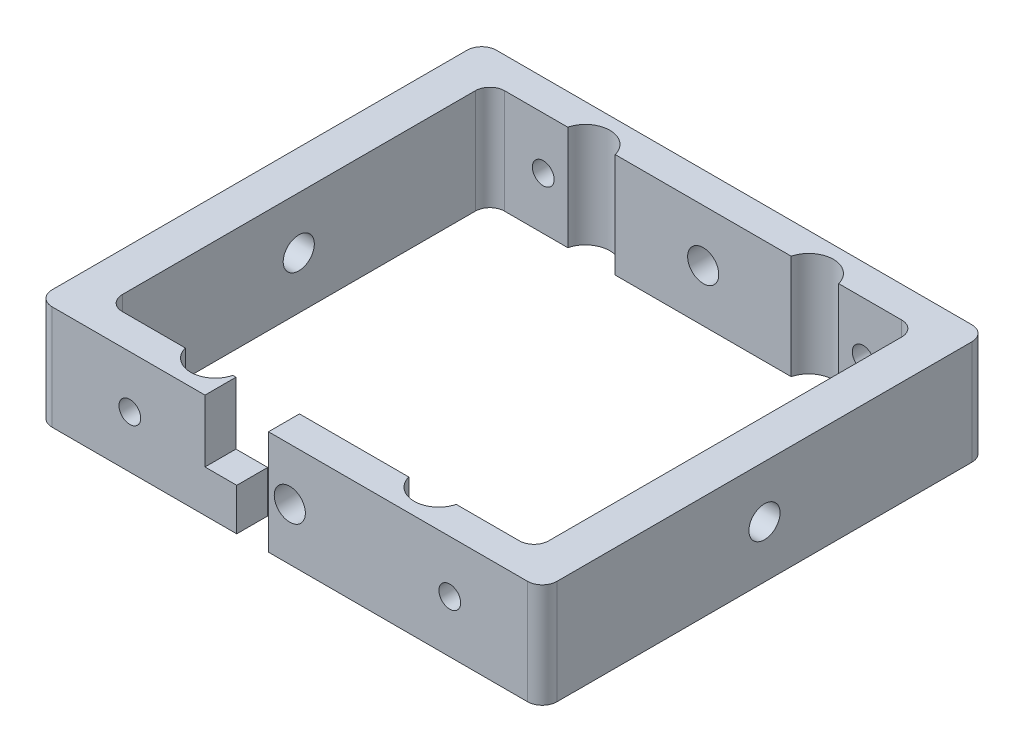
SolidWorks part; units mm, degrees
ref_plane "Front Plane" through (0, 0, 0) normal (0, 0, 1) x (1, 0, 0)
ref_plane "Top Plane" through (0, 0, 0) normal (0, 1, 0) x (1, 0, 0)
ref_plane "Right Plane" through (0, 0, 0) normal (1, 0, 0) x (0, 0, -1)
sketch "Sketch1" plane through (0, 0, 0) normal (0, 1, 0) x (1, 0, 0)
  line L1 (0, 0) -> (60, 0)
  line L2 (0, 0) -> (0, -6.32)
  line L3 (0, -6.32) -> (60, -6.32)
  line L4 (60, 0) -> (60, -6.32)
  dimension "D1" = 60
  dimension "D2" = 6.32
extrude "Boss-Extrude1" add sketch "Sketch1" along normal mid plane 21.28
sketch "Sketch2" plane through (0, 10.64, 0) normal (0, 1, 0) x (1, 0, 0)
  line L0 (0, 0) -> (0, -6.32) construction
  line L1 (0, -6.32) -> (60, -6.32) construction
  line L2 (60, -6.32) -> (60, 0) construction
  circle A0 centre (7.21, 1.25) radius 5
  circle A1 centre (52.79, 1.25) radius 5
  dimension "D1" = 7.21
  dimension "D3" = 7.21
  dimension "D2" = 7.57
  dimension "D4" = 7.57
extrude "Cut-Extrude1" cut sketch "Sketch2" against normal through all
sketch "Sketch3" plane through (60, 0, 0) normal (1, 0, 0) x (0, 0, -1)
  line L1 (-6.32, 10.64) -> (0, 10.64)
  line L2 (-6.32, 10.64) -> (-6.32, -10.64)
  line L3 (-6.32, -10.64) -> (0, -10.64)
  line L4 (0, 10.64) -> (0, -10.64)
extrude "Boss-Extrude2" add sketch "Sketch3" along normal blind 21.5
sketch "Sketch4" plane through (0, 0, 0) normal (-1, 0, 0) x (0, 0, 1)
  line L1 (0, 10.64) -> (6.32, 10.64)
  line L2 (0, 10.64) -> (0, -10.64)
  line L3 (0, -10.64) -> (6.32, -10.64)
  line L4 (6.32, 10.64) -> (6.32, -10.64)
extrude "Boss-Extrude3" add sketch "Sketch4" along normal blind 21.5
sketch "Sketch5" plane through (0, 0, 0) normal (0, 0, -1) x (-1, 0, 0)
  line L5 (-2.3688, -10.64) -> (21.5, -10.64) construction
  line L6 (21.5, 10.64) -> (13.5, 10.64)
  line L7 (21.5, 10.64) -> (21.5, -10.64)
  line L8 (21.5, -10.64) -> (13.5, -10.64)
  line L9 (13.5, 10.64) -> (13.5, -10.64)
  dimension "D1" = 8
extrude "Boss-Extrude6" add sketch "Sketch5" along normal blind 84.33
sketch "Sketch6" plane through (0, 0, 0) normal (0, 0, -1) x (-1, 0, 0)
  line L1 (-81.5, 10.64) -> (-73.5, 10.64)
  line L2 (-81.5, 10.64) -> (-81.5, -10.652)
  line L3 (-81.5, -10.652) -> (-73.5, -10.652)
  line L4 (-73.5, 10.64) -> (-73.5, -10.652)
  dimension "D1" = 8
extrude "Boss-Extrude7" add sketch "Sketch6" along normal blind 84.33
sketch "Sketch7" plane through (73.5, 0, 0) normal (-1, 0, 0) x (0, 0, 1)
  line L0 (-84.33, -10.652) -> (0, -10.652) construction
  line L1 (-84.33, 10.64) -> (-78.01, 10.64)
  line L2 (-84.33, 10.64) -> (-84.33, -10.652)
  line L3 (-84.33, -10.652) -> (-78.01, -10.652)
  line L4 (-78.01, 10.64) -> (-78.01, -10.652)
  dimension "D1" = 6.32
extrude "Boss-Extrude8" add sketch "Sketch7" along normal through all
sketch "Sketch9" plane through (0, 10.64, 0) normal (0, 1, 0) x (1, 0, 0)
  line L0 (-21.5, 84.33) -> (81.5, 84.33) construction
  circle A0 centre (7.21, 76.76) radius 5
  circle A1 centre (52.79, 76.76) radius 5
  dimension "D1" = 7.57
  dimension "D2" = 7.57
  dimension "D3" = 10
extrude "Cut-Extrude2" cut sketch "Sketch9" against normal through all
sketch "Sketch10" plane through (0, 0, -84.33) normal (0, 0, -1) x (-1, 0, 0)
  line L1 (-81.5, -10.64) -> (21.5, -10.64) construction
  line L2 (-30, -10.64) -> (-30, 10.64) construction
  line L3 (21.5, 10.64) -> (-81.5, 10.64) construction
  circle A0 centre (-62.6312, 0.005) radius 2.22
  circle A1 centre (2.6312, 0.005) radius 2.22
  dimension "D1" = 5
  dimension "D2" = 10.645
extrude "Cut-Extrude3" cut sketch "Sketch10" against normal through all
fillet "Fillet1" radius 3 8 edges at (81.5, 0, 6.32) (-21.5, 0, 6.32) (-13.5, 0, 0) (-21.5, -0.006, -84.33) (73.5, 0, 0) (81.5, -0.006, -84.33) (-13.5, 0, -78.01) (73.5, -0.006, -78.01)
sketch "Sketch13" plane through (0, 0, -84.33) normal (0, 0, -1) x (-1, 0, 0)
  line L1 (-78.5, 10.64) -> (-78.5, -10.652) construction
  line L2 (-78.5, -10.64) -> (18.5, -10.64) construction
  circle A0 centre (-30, 0.005) radius 3.175
  dimension "D1" = 48.5
  dimension "D3" = 6.35
  dimension "D2" = 10.645
extrude "Cut-Extrude4" cut sketch "Sketch13" against normal through all
sketch "Sketch16" plane through (0, -10.652, 0) normal (0, -1, 0) x (1, 0, 0)
  line L6 (78.5, -84.33) -> (-18.5, -84.33) construction
  line L7 (25.5729, -84.33) -> (12.6189, -84.33)
  line L8 (25.5729, -84.33) -> (25.5729, -78.01)
  line L9 (25.5729, -78.01) -> (12.6189, -78.01)
  line L10 (12.6189, -84.33) -> (12.6189, -78.01)
  line L11 (12.0512, -78.01) -> (47.9488, -78.01) construction
  dimension "D1" = 12.954
extrude "Cut-Extrude6" [suppressed] cut sketch "Sketch16" against normal mid plane 25.4
sketch "Sketch17" plane through (0, 10.64, 0) normal (0, 1, 0) x (1, 0, 0)
  line L1 (12.6964, 0.5862) -> (25.6504, 0.5862)
  line L2 (12.6964, 0.5862) -> (12.6964, -6.4457)
  line L3 (12.6964, -6.4457) -> (25.6504, -6.4457)
  line L4 (25.6504, 0.5862) -> (25.6504, -6.4457)
  dimension "D1" = 12.954
extrude "Cut-Extrude7" cut sketch "Sketch17" against normal mid plane 25.4
sketch "Sketch18" plane through (0, 0, 6.32) normal (0, 0, 1) x (1, 0, 0)
  line L0 (12.6964, -2.06) -> (25.6504, -2.06) construction
  line L1 (19.1734, -2.06) -> (25.6504, -2.06)
  line L2 (19.1734, -2.06) -> (19.1734, -10.64)
  line L3 (19.1734, -10.64) -> (25.6504, -10.64)
  line L4 (25.6504, -2.06) -> (25.6504, -10.64)
  line L5 (-18.5, -10.64) -> (78.5, -10.64) construction
extrude "Cut-Extrude8" cut sketch "Sketch18" against normal up to next
sketch "Sketch19" plane through (-21.5, 0, 0) normal (-1, 0, 0) x (0, 0, 1)
  line L0 (-81.33, 10.64) -> (-81.33, -10.652) construction
  circle A1 centre (-39.005, 0) radius 3.175
  dimension "D1" = 42.325
extrude "Cut-Extrude9" cut sketch "Sketch19" against normal through all
